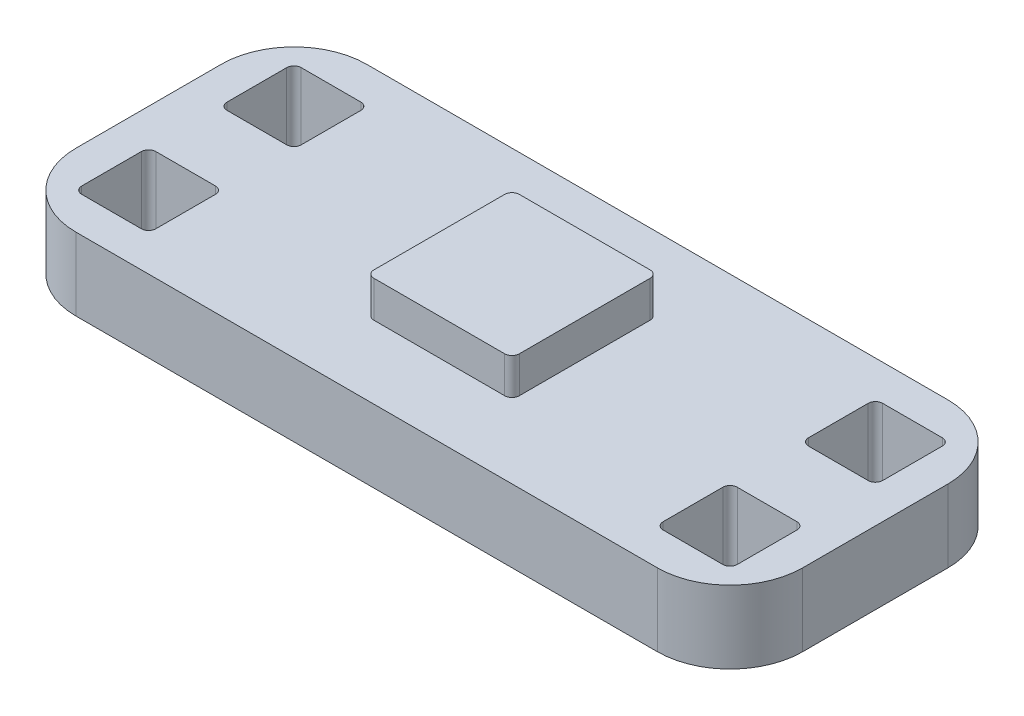
SolidWorks part; units mm, degrees
ref_plane "正面" through (0, 0, 0) normal (0, 0, 1) x (1, 0, 0)
ref_plane "平面" through (0, 0, 0) normal (0, 1, 0) x (1, 0, 0)
ref_plane "右側面" through (0, 0, 0) normal (1, 0, 0) x (0, 0, -1)
sketch "ｽｹｯﾁ1" plane through (0, 0, 0) normal (0, 1, 0) x (1, 0, 0)
  line L0 (0, 33.5662) -> (0, -33.8185) construction
  line L1 (-51.485, 0) -> (50.854, 0) construction
  line L2 (44.1, 15.1) -> (35.9, 15.1)
  line L3 (-50, -20) -> (50, -20)
  line L4 (-50, -20) -> (-50, 20)
  line L5 (-50, 20) -> (50, 20)
  line L6 (50, -20) -> (50, 20)
  line L7 (-50, -20) -> (50, 20) construction
  line L8 (-50, 20) -> (50, -20) construction
  line L9 (-44.1, 4.9) -> (-35.9, 4.9)
  line L10 (-45.1, 5.9) -> (-45.1, 14.1)
  line L11 (-44.1, 15.1) -> (-35.9, 15.1)
  line L12 (-34.9, 5.9) -> (-34.9, 14.1)
  line L13 (-45.1, 4.9) -> (-34.9, 15.1) construction
  line L14 (-45.1, 15.1) -> (-34.9, 4.9) construction
  line L15 (34.9, 5.9) -> (34.9, 14.1)
  line L16 (44.1, 4.9) -> (35.9, 4.9)
  line L17 (45.1, 5.9) -> (45.1, 14.1)
  line L18 (45.1, -5.9) -> (45.1, -14.1)
  line L19 (44.1, -4.9) -> (35.9, -4.9)
  line L20 (34.9, -5.9) -> (34.9, -14.1)
  line L21 (44.1, -15.1) -> (35.9, -15.1)
  line L22 (-44.1, -15.1) -> (-35.9, -15.1)
  line L23 (-34.9, -5.9) -> (-34.9, -14.1)
  line L24 (-44.1, -4.9) -> (-35.9, -4.9)
  line L25 (-45.1, -5.9) -> (-45.1, -14.1)
  line L26 (40, 15.1) -> (40, 4.9) construction
  line L27 (34.9, 10) -> (45.1, 10) construction
  line L28 (40, -4.9) -> (40, -15.1) construction
  line L29 (34.9, -10) -> (45.1, -10) construction
  line L30 (-40, -4.9) -> (-40, -15.1) construction
  line L31 (-45.1, -10) -> (-34.9, -10) construction
  arc A4 (-35.9, 15.1) -> (-34.9, 14.1) centre (-35.9, 14.1) cw
  arc A5 (-35.9, 4.9) -> (-34.9, 5.9) centre (-35.9, 5.9) ccw
  arc A6 (-44.1, 4.9) -> (-45.1, 5.9) centre (-44.1, 5.9) cw
  arc A7 (-45.1, 14.1) -> (-44.1, 15.1) centre (-44.1, 14.1) cw
  arc A8 (35.9, 15.1) -> (34.9, 14.1) centre (35.9, 14.1) ccw
  arc A9 (35.9, 4.9) -> (34.9, 5.9) centre (35.9, 5.9) cw
  arc A10 (44.1, 4.9) -> (45.1, 5.9) centre (44.1, 5.9) ccw
  arc A11 (45.1, 14.1) -> (44.1, 15.1) centre (44.1, 14.1) ccw
  arc A12 (45.1, -14.1) -> (44.1, -15.1) centre (44.1, -14.1) cw
  arc A13 (44.1, -4.9) -> (45.1, -5.9) centre (44.1, -5.9) cw
  arc A14 (35.9, -4.9) -> (34.9, -5.9) centre (35.9, -5.9) ccw
  arc A15 (35.9, -15.1) -> (34.9, -14.1) centre (35.9, -14.1) cw
  arc A16 (-35.9, -15.1) -> (-34.9, -14.1) centre (-35.9, -14.1) ccw
  arc A17 (-35.9, -4.9) -> (-34.9, -5.9) centre (-35.9, -5.9) cw
  arc A18 (-44.1, -4.9) -> (-45.1, -5.9) centre (-44.1, -5.9) ccw
  arc A19 (-45.1, -14.1) -> (-44.1, -15.1) centre (-44.1, -14.1) ccw
  point P5 (-40, 10)
  point P13 (0, 0)
  point P75 (40, 10)
  point P76 (40, -10)
  point P77 (0, 0)
  point P78 (50.354, 25.9346)
  dimension "D1" = 10.2
  dimension "D2" = 10.2
  dimension "D3" = 1
  dimension "D4" = 100
  dimension "D5" = 40
  dimension "D6" = 80
  dimension "D7" = 20
extrude "ﾎﾞｽ - 押し出し1" add sketch "ｽｹｯﾁ1" along normal blind 10
fillet "ﾌｨﾚｯﾄ1" radius 10 4 edges at (-50, 5, -20) (-50, 5, 20) (50, 5, -20) (50, 5, 20)
sketch "ｽｹｯﾁ2" plane through (0, 10, 0) normal (0, 1, 0) x (1, 0, 0)
  line L1 (-9, -10) -> (9, -10)
  line L2 (-10, -9) -> (-10, 9)
  line L3 (-9, 10) -> (9, 10)
  line L4 (10, -9) -> (10, 9)
  line L5 (-10, -10) -> (10, 10) construction
  line L6 (-10, 10) -> (10, -10) construction
  arc A0 (9, 10) -> (10, 9) centre (9, 9) cw
  arc A1 (9, -10) -> (10, -9) centre (9, -9) ccw
  arc A2 (-9, -10) -> (-10, -9) centre (-9, -9) cw
  arc A3 (-10, 9) -> (-9, 10) centre (-9, 9) cw
  point P0 (0, 0)
  dimension "D3" = 1
  dimension "D1" = 20
  dimension "D2" = 20
extrude "ﾎﾞｽ - 押し出し2" add sketch "ｽｹｯﾁ2" along normal blind 5
